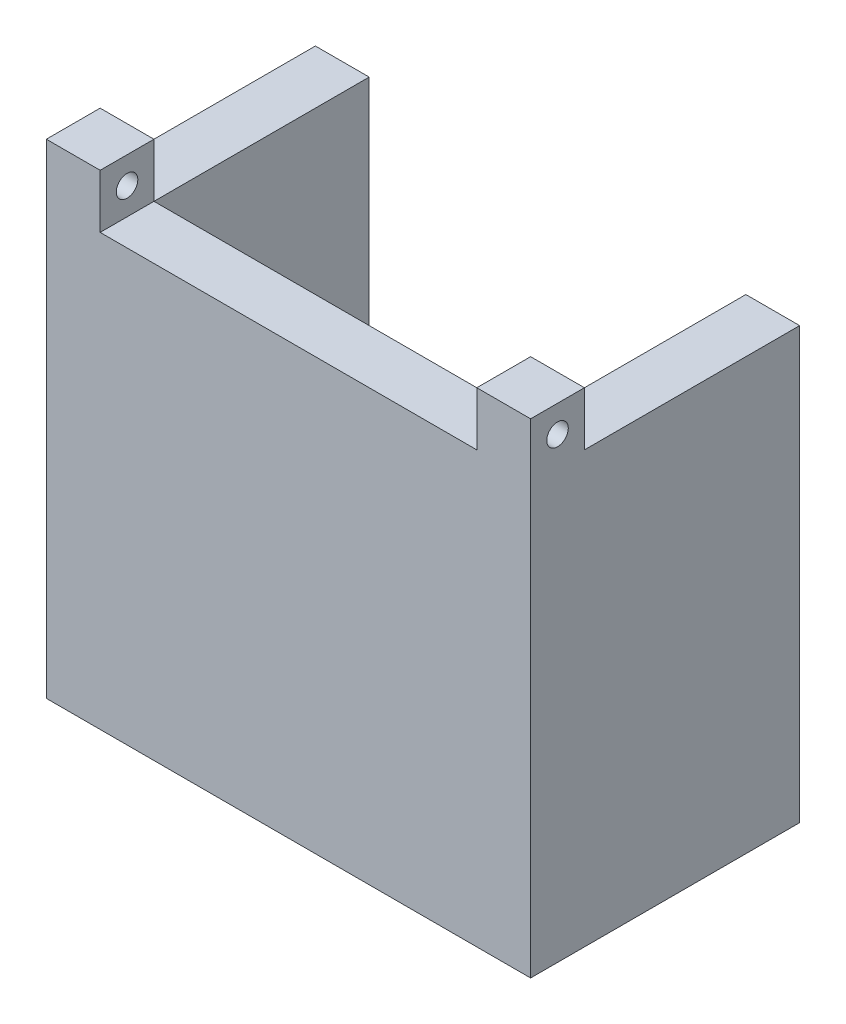
SolidWorks part; units mm, degrees
ref_plane "前基準面" through (0, 0, 0) normal (0, 0, 1) x (1, 0, 0)
ref_plane "上基準面" through (0, 0, 0) normal (0, 1, 0) x (1, 0, 0)
ref_plane "右基準面" through (0, 0, 0) normal (1, 0, 0) x (0, 0, -1)
sketch "草圖1" plane through (0, 0, 0) normal (0, 0, 1) x (1, 0, 0)
  line L1 (-22.5, 22.5) -> (22.5, 22.5)
  line L2 (-22.5, 22.5) -> (-22.5, -22.5)
  line L3 (-22.5, -22.5) -> (22.5, -22.5)
  line L4 (22.5, 22.5) -> (22.5, -22.5)
  line L5 (-22.5, 22.5) -> (22.5, -22.5) construction
  line L6 (-22.5, -22.5) -> (22.5, 22.5) construction
  point P0 (0, 0)
  dimension "D1" = 45
  dimension "D2" = 45
extrude "填料-伸長1" add sketch "草圖1" along normal blind 5
sketch "草圖2" plane through (22.5, 0, 0) normal (1, 0, 0) x (0, 0, -1)
  line L0 (0, -22.5) -> (0, 22.5) construction
  line L1 (-5, 22.5) -> (0, 22.5)
  line L2 (-5, 22.5) -> (-5, 17.5)
  line L3 (-5, 17.5) -> (0, 17.5)
  line L4 (0, 22.5) -> (0, 17.5)
  circle A0 centre (-2.5, 20) radius 1
  circle A1 centre (-2.5, 20) radius 2
  point P10 (-5, 20)
  point P11 (-2.5, 17.5)
  dimension "D2" = 4
  dimension "D3" = 2
  dimension "D1" = 5
extrude "除料-伸長2" cut sketch "草圖2" against normal blind 5 contours A0
sketch "草圖3" plane through (0, 0, 0) normal (0, 0, -1) x (-1, 0, 0)
  line L0 (-22.5, 22.5) -> (22.5, 22.5) construction
  line L1 (-17.5, 22.5) -> (17.5, 22.5)
  line L2 (-17.5, 22.5) -> (-17.5, 17.5)
  line L3 (-17.5, 17.5) -> (17.5, 17.5)
  line L4 (17.5, 22.5) -> (17.5, 17.5)
  line L5 (-22.5, -22.5) -> (-22.5, 22.5) construction
  line L6 (22.5, 22.5) -> (22.5, -22.5) construction
  dimension "D1" = 5
  dimension "D2" = 5
  dimension "D3" = 5
extrude "除料-伸長3" cut sketch "草圖3" against normal through all
mirror "鏡射1" about plane through (0, 0, 0) normal (1, 0, 0) of "除料-伸長2"
sketch "草圖4" plane through (0, 0, 0) normal (0, 0, -1) x (-1, 0, 0)
  line L1 (-22.5, -22.5) -> (-17.5, -22.5)
  line L2 (-22.5, -22.5) -> (-22.5, 17.5)
  line L3 (-22.5, 17.5) -> (-17.5, 17.5)
  line L4 (-17.5, -22.5) -> (-17.5, 17.5)
extrude "填料-伸長2" add sketch "草圖4" along normal blind 20
mirror "鏡射2" about plane through (0, 0, 0) normal (1, 0, 0) of "填料-伸長2"
